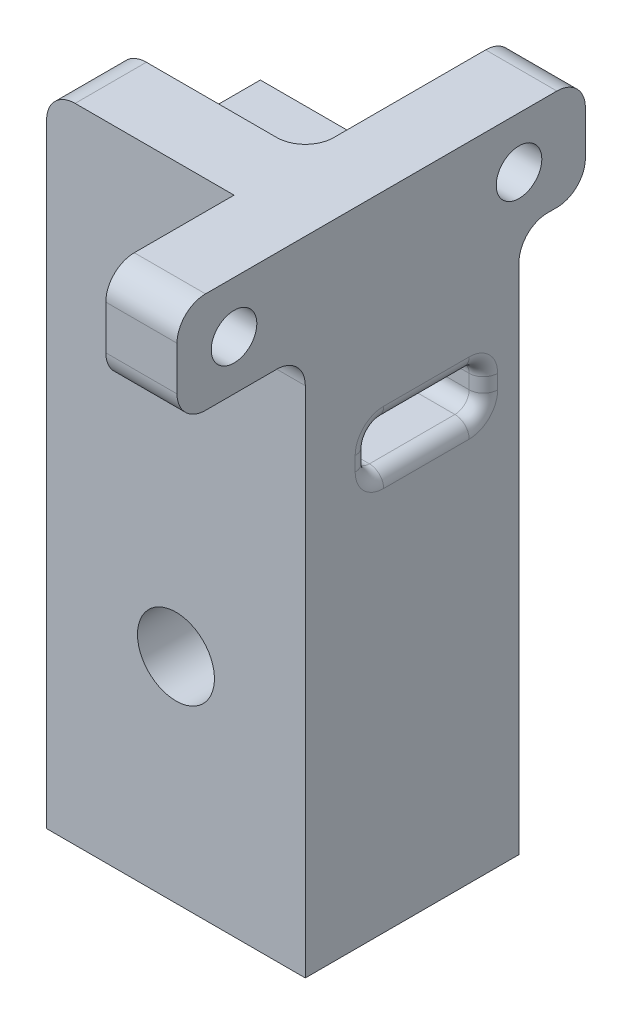
SolidWorks part; units mm, degrees
ref_plane "Front Plane" through (0, 0, 0) normal (0, 0, 1) x (1, 0, 0)
ref_plane "Top Plane" through (0, 0, 0) normal (0, 1, 0) x (1, 0, 0)
ref_plane "Right Plane" through (0, 0, 0) normal (1, 0, 0) x (0, 0, -1)
sketch "Sketch1" plane through (0, 0, 0) normal (0, 0, 1) x (1, 0, 0)
  line L0 (0, -10.4775) -> (0, 10.4775) construction
  line L1 (-11.5282, -47.625) -> (11.5282, -47.625)
  line L2 (-11.5282, -47.625) -> (-11.5282, 47.625)
  line L3 (-11.5282, 47.625) -> (11.5282, 47.625)
  line L4 (11.5282, -47.625) -> (11.5282, 47.625)
  line L5 (-11.5282, -47.625) -> (11.5282, 47.625) construction
  line L6 (-11.5282, 47.625) -> (11.5282, -47.625) construction
  line L7 (-7.9121, 16.6878) -> (7.9121, 16.6878)
  line L8 (-7.9121, 16.6878) -> (-7.9121, 44.45)
  line L9 (-7.9121, 44.45) -> (7.9121, 44.45)
  line L10 (7.9121, 16.6878) -> (7.9121, 44.45)
  line L11 (-7.9121, 16.6878) -> (7.9121, 44.45) construction
  line L12 (-7.9121, 44.45) -> (7.9121, 16.6878) construction
  circle A0 centre (-5.3721, 41.91) radius 1.27
  circle A1 centre (5.3721, 19.2278) radius 1.27
  point P0 (0, 0)
  point P6 (0, 30.5689)
  dimension "D4" = 2.54
  dimension "D5" = 2.54
  dimension "D6" = 2.54
  dimension "D7" = 2.54
  dimension "D8" = 2.54
  dimension "D1" = 95.25
  dimension "D2" = 27.7622
  dimension "D3" = 15.8242
  dimension ".1" = 2.54
  dimension "D9" = 3.175
extrude "Boss-Extrude1" add sketch "Sketch1" along normal blind 6.35 contours L1 L4 L3 L2 L10 L7 L8 L9 | L7 L10 L9 L8 A1 A0 | A0 | A1
sketch "Sketch2" plane through (0, 0, 0) normal (0, 0, -1) x (-1, 0, 0)
  line L0 (11.5282, -47.625) -> (11.5282, 47.625) construction
  line L1 (-11.5282, -47.625) -> (11.5282, -47.625)
  line L2 (-11.5282, -47.625) -> (-11.5282, 0.635)
  line L3 (-11.5282, 0.635) -> (11.5282, 0.635)
  line L4 (11.5282, -47.625) -> (11.5282, 0.635)
  dimension "D1" = 48.26
extrude "Boss-Extrude2" add sketch "Sketch2" along normal blind 12.7
sketch "Sketch5" plane through (11.5282, 0, 0) normal (1, 0, 0) x (0, 0, -1)
  line L0 (12.7, 0.635) -> (0, 0.635) construction
  line L1 (-0.635, -12.065) -> (9.525, -12.065)
  line L2 (-0.635, -12.065) -> (-0.635, -8.255)
  line L3 (-0.635, -8.255) -> (9.525, -8.255)
  line L4 (9.525, -12.065) -> (9.525, -8.255)
  line L5 (-0.635, -12.065) -> (9.525, -8.255) construction
  line L6 (-0.635, -8.255) -> (9.525, -12.065) construction
  line L7 (12.7, 0.635) -> (12.7, -47.625) construction
  point P0 (4.445, -10.16)
  dimension "D1" = 8.89
  dimension "D2" = 3.175
  dimension "D3" = 10.16
  dimension "D4" = 3.81
extrude "Cut-Extrude2" cut sketch "Sketch5" against normal through all
sketch "Sketch6" plane through (0, 0, -12.7) normal (0, 0, -1) x (-1, 0, 0)
  line L0 (0, 3.4925) -> (0, -3.4925) construction
  line L1 (-11.5282, -47.625) -> (11.5282, -47.625) construction
  circle A0 centre (0, -28.575) radius 3.429
  dimension "D1" = 19.05
  dimension "D2" = 6.858
extrude "Cut-Extrude3" cut sketch "Sketch6" against normal through all
fillet "Fillet2" radius 1.27 12 edges at (-11.5282, -10.16, -9.525) (-11.5282, -12.065, -4.445) (-11.5282, -10.16, 0.635) (-11.5282, -8.255, -4.445) (0, -8.255, -9.525) (0, -12.065, -9.525) (0, -8.255, 0.635) (0, -12.065, 0.635) (11.5282, -10.16, -9.525) (11.5282, -12.065, -4.445) (11.5282, -10.16, 0.635) (11.5282, -8.255, -4.445)
sketch "Sketch8" plane through (-11.5282, 0, 0) normal (-1, 0, 0) x (0, 0, 1)
  line L1 (6.35, 47.625) -> (0, 47.625)
  line L2 (6.35, 47.625) -> (6.35, 6.9863)
  line L3 (6.35, 6.9863) -> (0, 6.9863)
  line L4 (0, 47.625) -> (0, 6.9863)
  line L5 (0, -12.681) -> (0, 12.681) construction
extrude "Boss-Extrude3" add sketch "Sketch8" along normal blind 6.35
sketch "Sketch9" plane through (0, 0, 0) normal (0, 0, 1) x (1, 0, 0)
  line L0 (-17.8782, 47.625) -> (-17.8782, 6.9863) construction
  line L7 (-17.8782, 10.3378) -> (-2.054, 10.3378)
  line L8 (-17.8782, 10.3378) -> (-17.8782, 38.1)
  line L9 (-17.8782, 38.1) -> (-2.054, 38.1)
  line L10 (-2.054, 10.3378) -> (-2.054, 38.1)
  line L11 (-17.8782, 10.3378) -> (-2.054, 38.1) construction
  line L12 (-17.8782, 38.1) -> (-2.054, 10.3378) construction
  circle A0 centre (-15.3382, 35.56) radius 1.905
  circle A1 centre (-4.594, 12.8778) radius 1.905
  point P0 (0, 0)
  point P6 (-9.9661, 24.2189)
  dimension "D4" = 3.81
  dimension "D5" = 3.81
  dimension "D6" = 2.54
  dimension "D7" = 2.54
  dimension "D8" = 2.54
  dimension "D1" = 0
  dimension "D2" = 27.7622
  dimension "D3" = 15.8242
  dimension ".1" = 2.54
extrude "Cut-Extrude4" cut sketch "Sketch9" along normal through all contours A1 | A0
fillet "Fillet4" radius 2.54 2 edges at (-17.8782, 47.625, 3.175) (11.5282, 47.625, 3.175)
sketch "Sketch12" plane through (11.5282, 0, 0) normal (1, 0, 0) x (0, 0, -1)
  line L0 (-6.35, -47.625) -> (-6.35, 45.085) construction
  line L1 (-6.35, 0.635) -> (18.6137, 0.635)
  line L4 (18.6137, 0.635) -> (18.6137, 9.6272)
  line L5 (-17.782, 9.6272) -> (18.6137, 9.6272)
  line L6 (-6.35, 0.635) -> (-17.782, 0.635)
  line L9 (-17.782, 0.635) -> (-17.782, 9.6272)
extrude "Boss-Extrude7" add sketch "Sketch12" against normal blind 6.35
fillet "Fillet5" radius 2.54 3 edges at (8.3532, 0.635, -12.7) (5.1782, 5.1311, 0) (8.3532, 0.635, 6.35)
fillet "Fillet6" radius 2.54 1 edges at (5.1782, -0.635, -12.7)
sketch "Sketch13" plane through (11.5282, 0, 0) normal (1, 0, 0) x (0, 0, -1)
  circle A0 centre (-12.702, 5.0507) radius 2.032
  circle A1 centre (12.698, 5.0507) radius 2.032
  dimension "D1" = 4.064
  dimension "D2" = 4.064
  dimension "D3" = 25.4
extrude "Cut-Extrude5" cut sketch "Sketch13" against normal blind 6.35
fillet "Fillet7" radius 2.54 4 edges at (8.3532, 0.635, -18.6137) (8.3532, 9.6272, -18.6137) (8.3532, 0.635, 17.782) (8.3532, 9.6272, 17.782)
sketch "Sketch14" plane through (11.5282, 0, 0) normal (1, 0, 0) x (0, 0, -1)
  line L1 (-6.35, 9.6272) -> (2.4578, 9.6272)
  line L2 (-6.35, 9.6272) -> (-6.35, 48.7021)
  line L3 (-6.35, 48.7021) -> (2.4578, 48.7021)
  line L4 (2.4578, 9.6272) -> (2.4578, 48.7021)
extrude "Cut-Extrude6" cut sketch "Sketch14" against normal blind 45.212
sketch "Sketch15" plane through (0, 6.9863, 0) normal (0, -1, 0) x (1, 0, 0)
  line L1 (-11.5282, 6.35) -> (-17.8782, 6.35)
  line L2 (-11.5282, 6.35) -> (-11.5282, 0)
  line L3 (-11.5282, 0) -> (-17.8782, 0)
  line L4 (-17.8782, 6.35) -> (-17.8782, 0)
extrude "Cut-Extrude7" cut sketch "Sketch15" against normal blind 7.112
fillet "Fillet8" radius 2.54 1 edges at (-11.5282, 9.6272, 3.175)
